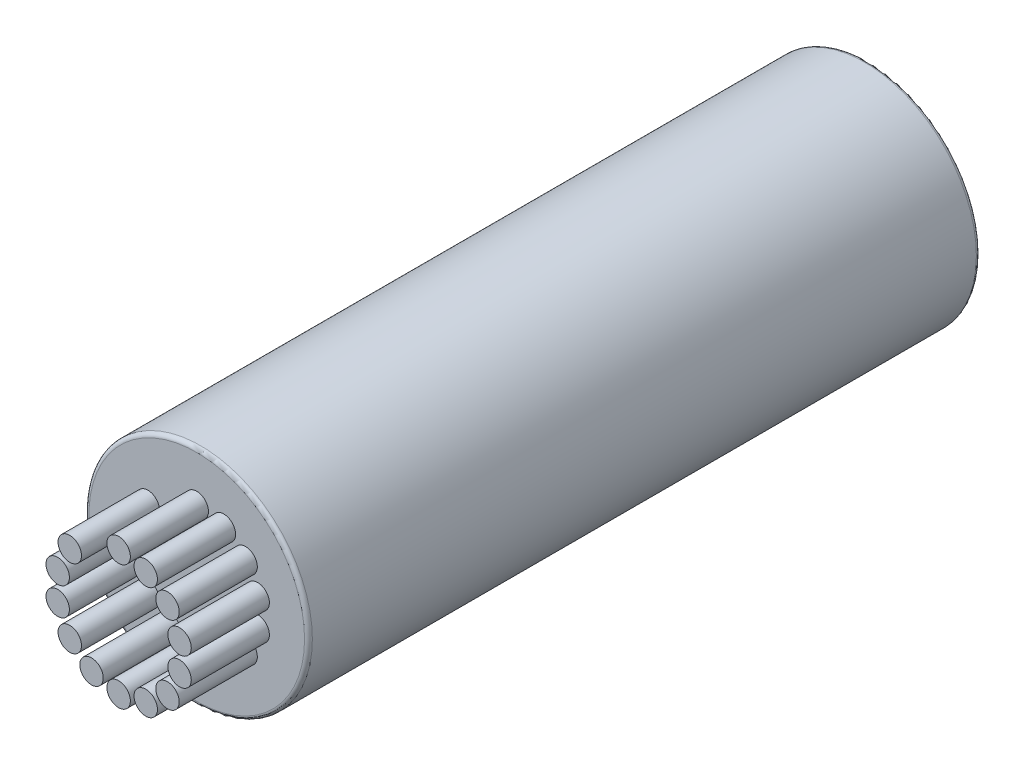
SolidWorks part; units mm, degrees
ref_plane "Front Plane" through (0, 0, 0) normal (0, 0, 1) x (1, 0, 0)
ref_plane "Top Plane" through (0, 0, 0) normal (0, 1, 0) x (1, 0, 0)
ref_plane "Right Plane" through (0, 0, 0) normal (1, 0, 0) x (0, 0, -1)
sketch "Sketch1" plane through (0, 0, 0) normal (0, 0, 1) x (1, 0, 0)
  circle A0 centre (0, 0) radius 7.15
  dimension "D1" = 14.3
extrude "Boss-Extrude1" add sketch "Sketch1" along normal blind 43
sketch "Sketch2" plane through (0, 0, 0) normal (0, 0, -1) x (-1, 0, 0)
  circle A0 centre (0, 0) radius 5
  dimension "D1" = 10
extrude "Cut-Extrude1" cut sketch "Sketch2" against normal blind 0.1
sketch "Sketch3" plane through (0, 0, 43) normal (0, 0, 1) x (1, 0, 0)
  circle A13 centre (0, 4) radius 0.75
  circle A14 centre (1.7355, 3.6039) radius 0.75
  circle A15 centre (3.1273, 2.494) radius 0.75
  circle A16 centre (3.8997, 0.8901) radius 0.75
  circle A17 centre (3.8997, -0.8901) radius 0.75
  circle A18 centre (3.1273, -2.494) radius 0.75
  circle A19 centre (1.7355, -3.6039) radius 0.75
  circle A20 centre (0, -4) radius 0.75
  circle A21 centre (-1.7355, -3.6039) radius 0.75
  circle A22 centre (-3.1273, -2.494) radius 0.75
  circle A23 centre (-3.8997, -0.8901) radius 0.75
  circle A49 centre (-3.8997, 0.8901) radius 0.75
  circle A50 centre (-3.1273, 2.494) radius 0.75
  circle A52 centre (-1.7355, 3.6039) radius 0.75 [skipped]
  point P30 (0, 0)
  point P54 (0, 0)
  dimension "D3" = 14
  dimension "D2" = 1.5
  dimension "D1" = 4
extrude "Boss-Extrude2" add sketch "Sketch3" along normal blind 5
fillet "Fillet1" radius 0.25 2 edges at (7.15, 0, 43) (7.15, 0, 0)
